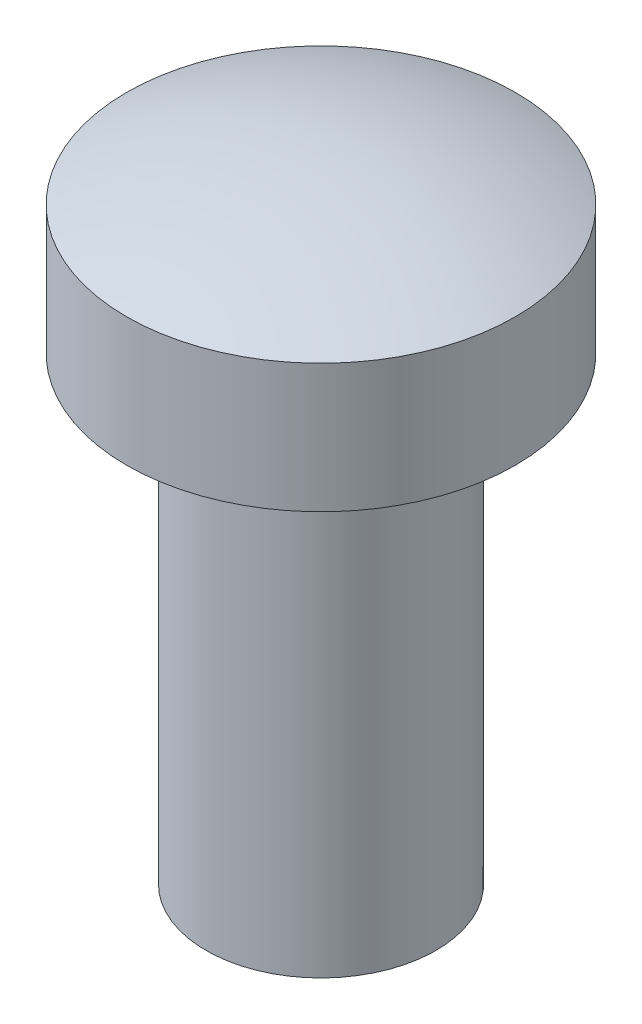
SolidWorks part; units mm, degrees
ref_plane "前基準面" through (0, 0, 0) normal (0, 0, 1) x (1, 0, 0)
ref_plane "上基準面" through (0, 0, 0) normal (0, 1, 0) x (1, 0, 0)
ref_plane "右基準面" through (0, 0, 0) normal (1, 0, 0) x (0, 0, -1)
sketch "草圖1" plane through (0, 0, 0) normal (0, 0, 1) x (1, 0, 0)
  line L0 (0, 0) -> (0, 2.7382)
  line L2 (-0.8453, 2) -> (-0.5, 2)
  line L3 (-0.5, 2) -> (-0.5, 0)
  line L4 (-0.5, 0) -> (0, 0)
  line L5 (-0.8453, 2) -> (-0.8453, 2.5593)
  arc A0 (0, 2.7382) -> (-0.8453, 2.5593) centre (0, 0.6521) ccw
  dimension "D4" = 2.0862
  dimension "D1" = 0.5
  dimension "D2" = 2
  dimension "D3" = 0.8453
  dimension "D5" = 0.7382
revolve "旋轉1" add sketch "草圖1" angle 360 about L0
cosmetic thread "裝飾螺紋線1" parameters "D1"=0.7, "D2"=0.711
